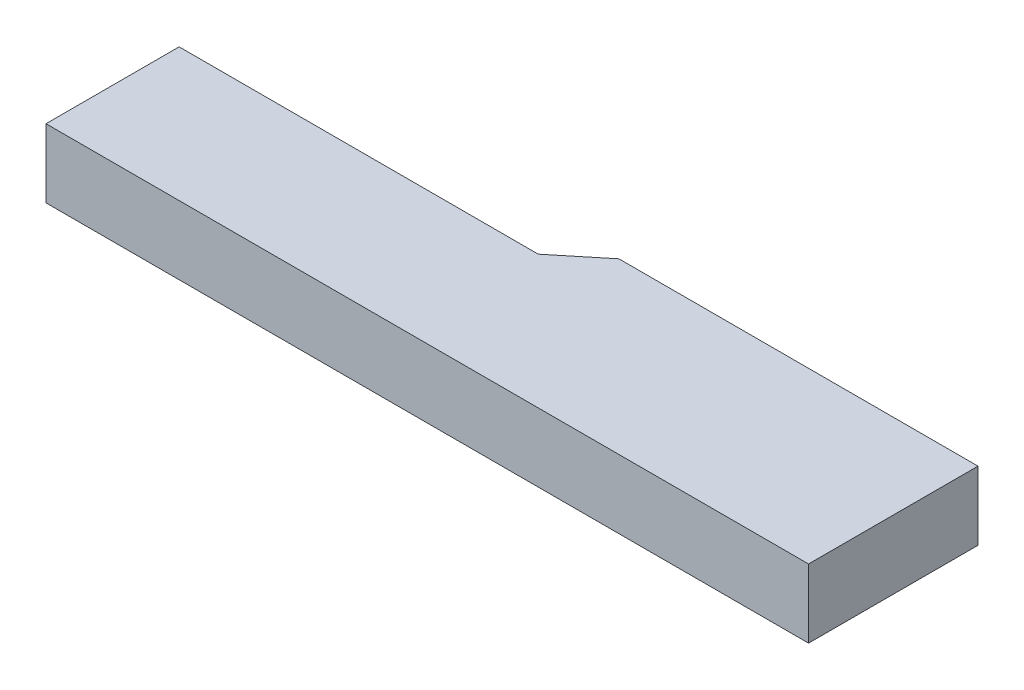
SolidWorks part; units mm, degrees
material "黄铜"
ref_plane "前视基准面" through (0, 0, 0) normal (0, 0, 1) x (1, 0, 0)
ref_plane "上视基准面" through (0, 0, 0) normal (0, 1, 0) x (1, 0, 0)
ref_plane "右视基准面" through (0, 0, 0) normal (1, 0, 0) x (0, 0, -1)
sketch "草图1" plane through (0, 0, 0) normal (0, 1, 0) x (1, 0, 0)
  line L1 (7.6528, 19.9923) -> (96.6528, 19.9923)
  line L2 (-92.3472, 10.9923) -> (-92.3472, -22.0077)
  line L3 (-92.3472, -22.0077) -> (96.6528, -22.0077)
  line L4 (96.6528, 19.9923) -> (96.6528, -22.0077)
  line L5 (7.6528, 19.9923) -> (-3.3472, 10.9923)
  line L6 (-3.3472, 10.9923) -> (-92.3472, 10.9923)
  point P4 (7.6528, 19.9923)
  dimension "D1" = 189
  dimension "D2" = 42
  dimension "D3" = 89
extrude "凸台-拉伸4" add sketch "草图1" along normal blind 17 contours L3 L4 L1 L5 L6 L2
